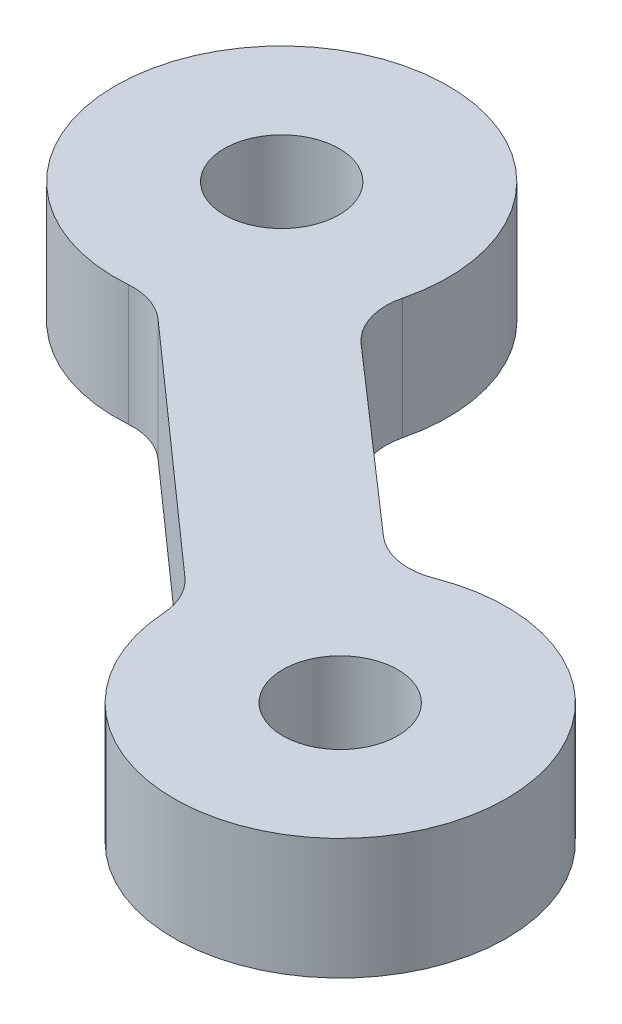
SolidWorks part; units mm, degrees
ref_plane "Front Plane" through (0, 0, 0) normal (0, 0, 1) x (1, 0, 0)
ref_plane "Top Plane" through (0, 0, 0) normal (0, 1, 0) x (1, 0, 0)
ref_plane "Right Plane" through (0, 0, 0) normal (1, 0, 0) x (0, 0, -1)
sketch "Sketch2" plane through (0, 0, 0) normal (0, 1, 0) x (1, 0, 0)
  line L7 (94.9551, 38.1723) -> (87.0277, 45.1049)
  line L12 (92.5032, 34.0063) -> (83.2947, 42.1711)
  line L13 (83.2947, 42.1711) -> (92.5032, 34.0063)
  line L18 (87.0277, 45.1049) -> (94.9551, 38.1723)
  arc A0 (87.0277, 45.1049) -> (83.2947, 42.1711) centre (82.0956, 47.5388) ccw
  circle A7 centre (82.0956, 47.5388) radius 1.9
  arc A10 (92.5032, 34.0063) -> (94.9551, 38.1723) centre (97.9869, 33.5834) ccw
  circle A17 centre (97.9869, 33.5834) radius 1.9
extrude "Boss-Extrude1" add sketch "Sketch2" along normal blind 4
fillet "Fillet1" radius 2 4 edges at (83.2947, 2, -42.1711) (92.5032, 2, -34.0063) (87.0277, 2, -45.1049) (94.9551, 2, -38.1723)
